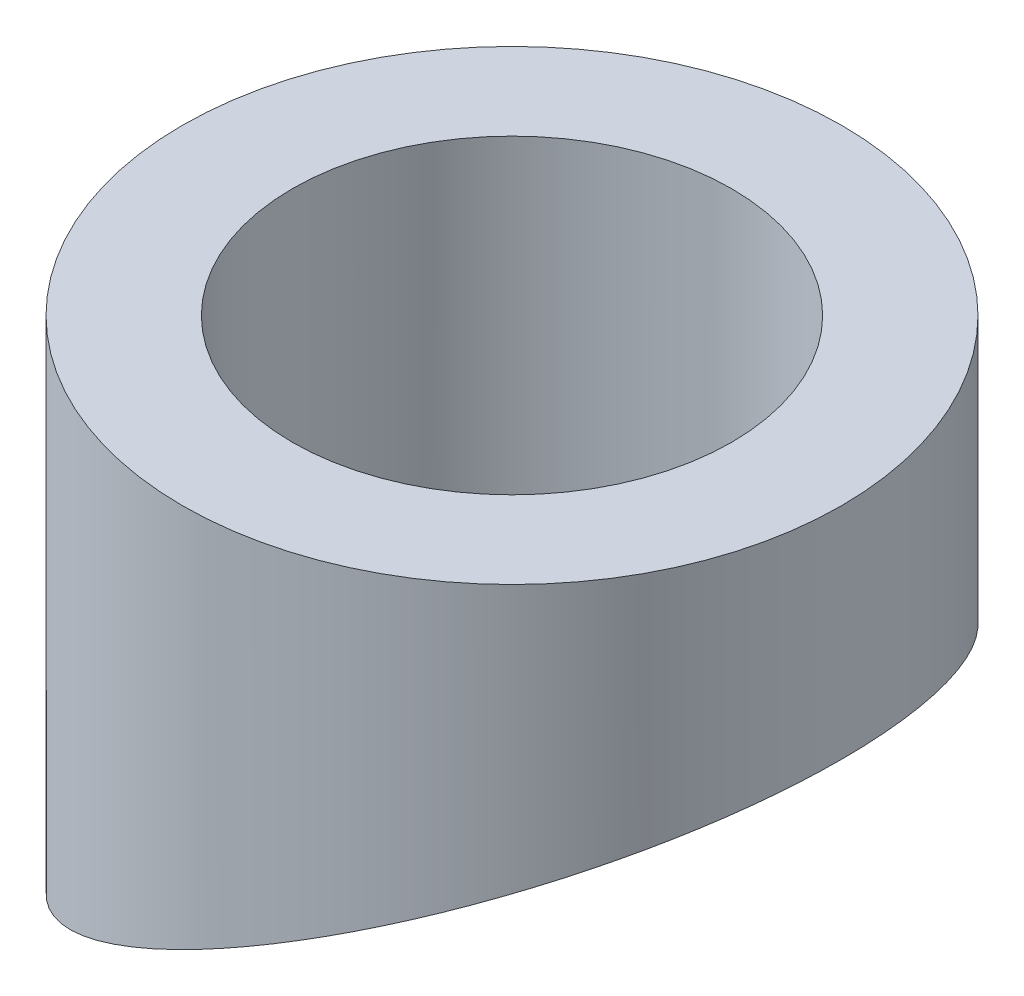
SolidWorks part; units mm, degrees
ref_plane "Front Plane" through (0, 0, 0) normal (0, 0, 1) x (1, 0, 0)
ref_plane "Top Plane" through (0, 0, 0) normal (0, 1, 0) x (1, 0, 0)
ref_plane "Right Plane" through (0, 0, 0) normal (1, 0, 0) x (0, 0, -1)
sketch "Sketch1" plane through (0, 0, 0) normal (0, 1, 0) x (1, 0, 0)
  circle A0 centre (0, 0) radius 6
  circle A1 centre (0, 0) radius 9
  dimension "D1" = 12
  dimension "D2" = 3
extrude "Boss-Extrude1" add sketch "Sketch1" along normal blind 15
sketch "Sketch3" plane through (0, 0, 0) normal (0, 0, 1) x (1, 0, 0)
  line L0 (-9, 0) -> (9, 9)
  line L1 (9, 0) -> (9, 15) construction
  line L2 (9, 9) -> (9, 0)
  line L3 (9, 0) -> (-9, 0)
  dimension "D1" = 9
extrude "Cut-Extrude1" cut sketch "Sketch3" against normal mid plane 30
